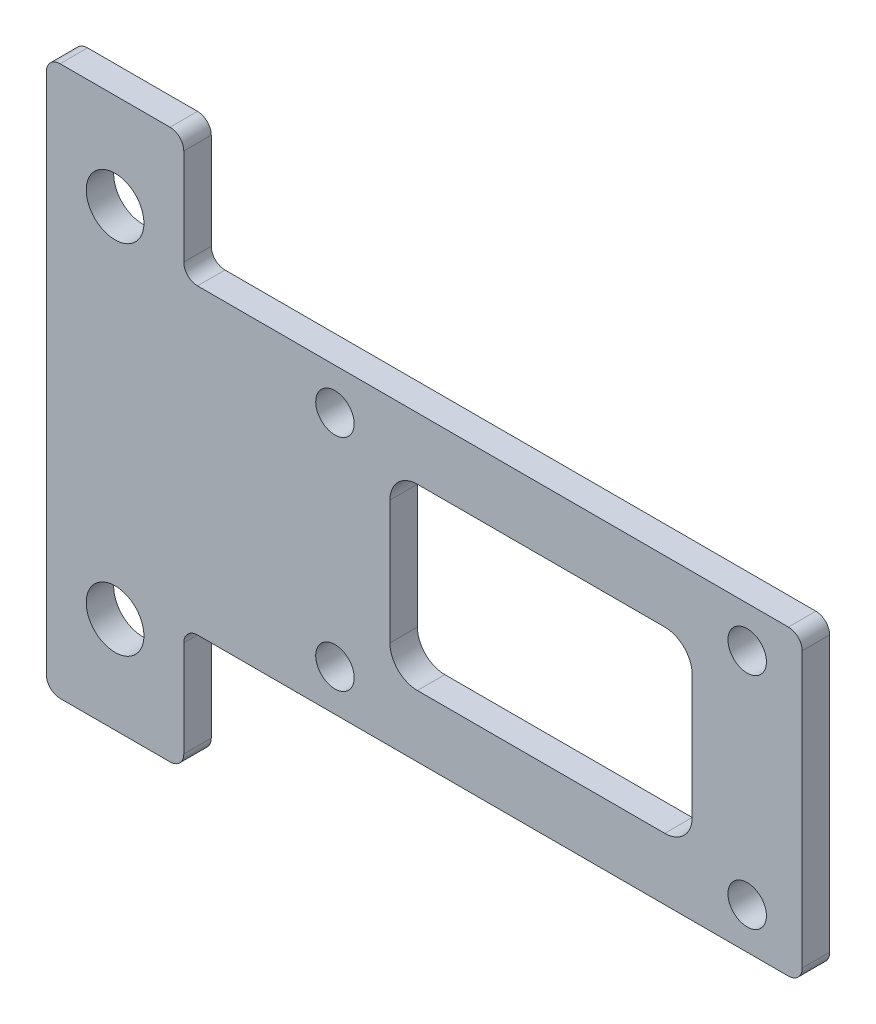
SolidWorks part; units mm, degrees
material "Thornel Mat VMA"
ref_plane "前视基准面" through (0, 0, 0) normal (0, 0, 1) x (1, 0, 0)
ref_plane "上视基准面" through (0, 0, 0) normal (0, 1, 0) x (1, 0, 0)
ref_plane "右视基准面" through (0, 0, 0) normal (1, 0, 0) x (0, 0, -1)
sketch "草图1" plane through (0, 0, 0) normal (0, 0, 1) x (1, 0, 0)
  line L0 (87.5, -11) -> (87.5, -51)
  line L1 (94.5, -11) -> (28, -11) construction
  line L2 (28, -51) -> (94.5, -51) construction
  line L3 (87.5, -51) -> (97.5, -51)
  line L4 (97.5, -51) -> (97.5, -42)
  line L5 (97.5, -42) -> (142.5, -42)
  line L6 (96.5, -31) -> (142.5, -31) construction
  line L7 (96.5, -39.4019) -> (96.5, -22.5981) construction
  line L8 (142.5, -42) -> (142.5, -20)
  line L9 (97.5, -20) -> (142.5, -20)
  line L10 (87.5, -11) -> (97.5, -11)
  line L11 (97.5, -11) -> (97.5, -20)
  line L13 (132.5, -37.5) -> (114.5, -37.5)
  line L14 (134.5, -35.5) -> (134.5, -26.5)
  line L15 (132.5, -24.5) -> (114.5, -24.5)
  line L16 (112.5, -35.5) -> (112.5, -26.5)
  line L17 (134.5, -37.5) -> (112.5, -24.5) construction
  line L18 (134.5, -24.5) -> (112.5, -37.5) construction
  circle A0 centre (92.5, -18) radius 2.1
  circle A1 centre (92.5, -44) radius 2.1
  circle A2 centre (138.5, -39) radius 1.4
  circle A3 centre (108.5, -39) radius 1.4
  circle A4 centre (108.5, -23) radius 1.4
  circle A5 centre (138.5, -23) radius 1.4
  arc A6 (114.5, -37.5) -> (112.5, -35.5) centre (114.5, -35.5) cw
  arc A7 (132.5, -37.5) -> (134.5, -35.5) centre (132.5, -35.5) ccw
  arc A8 (134.5, -26.5) -> (132.5, -24.5) centre (132.5, -26.5) ccw
  arc A9 (114.5, -24.5) -> (112.5, -26.5) centre (114.5, -26.5) ccw
  point P33 (123.5, -31)
  dimension "D1" = 4.2
  dimension "D2" = 4.2
  dimension "D7" = 2.8
  dimension "D8" = 2.8
  dimension "D12" = 2
  dimension "D3" = 5
  dimension "D4" = 10
  dimension "D5" = 9
  dimension "D6" = 45
  dimension "D9" = 19
  dimension "D10" = 22
  dimension "D11" = 13
extrude "凸台-拉伸1" add sketch "草图1" along normal blind 2
fillet "圆角1" radius 1 8 edges at (142.5, -20, 1) (142.5, -42, 1) (97.5, -42, 1) (97.5, -51, 1) (87.5, -51, 1) (87.5, -11, 1) (97.5, -20, 1) (97.5, -11, 1)
